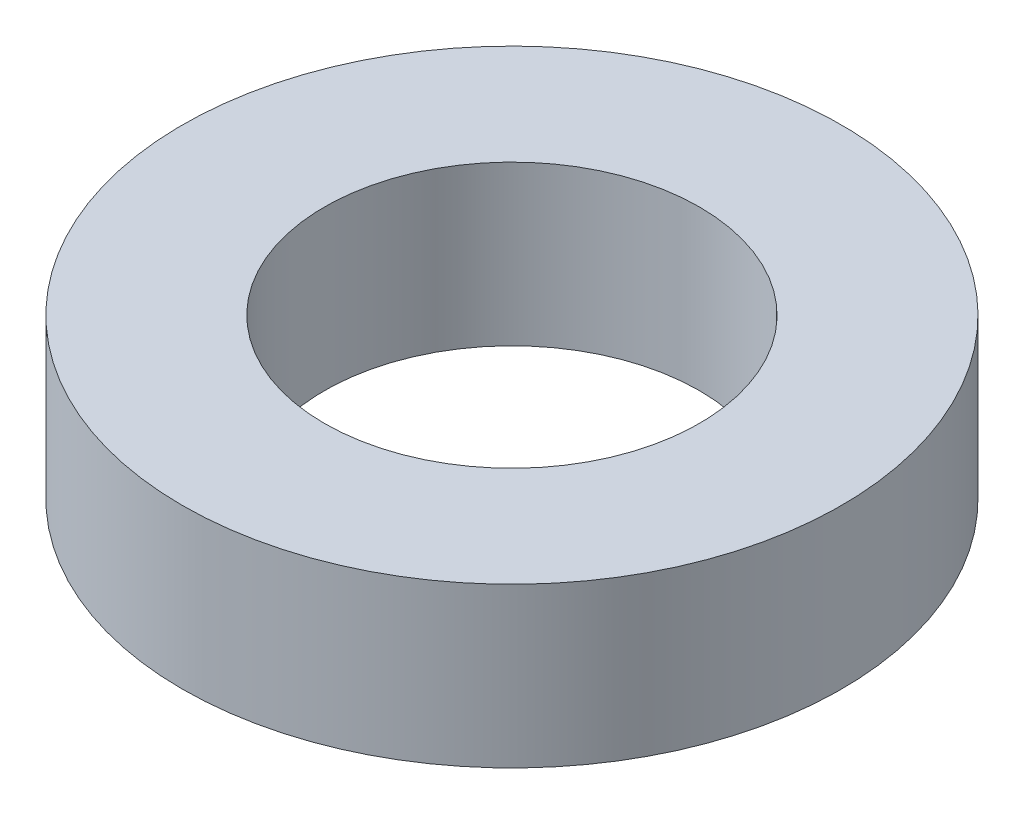
SolidWorks part; units mm, degrees
ref_plane "Спереди" through (0, 0, 0) normal (0, 0, 1) x (1, 0, 0)
ref_plane "Сверху" through (0, 0, 0) normal (0, 1, 0) x (1, 0, 0)
ref_plane "Справа" through (0, 0, 0) normal (1, 0, 0) x (0, 0, -1)
sketch "Эскиз1" plane through (0, 0, 0) normal (0, 1, 0) x (1, 0, 0)
  circle A0 centre (0, 0) radius 1.65
  circle A1 centre (0, 0) radius 2.9
extrude "Бобышка-Вытянуть1" add sketch "Эскиз1" along normal blind 1.4
